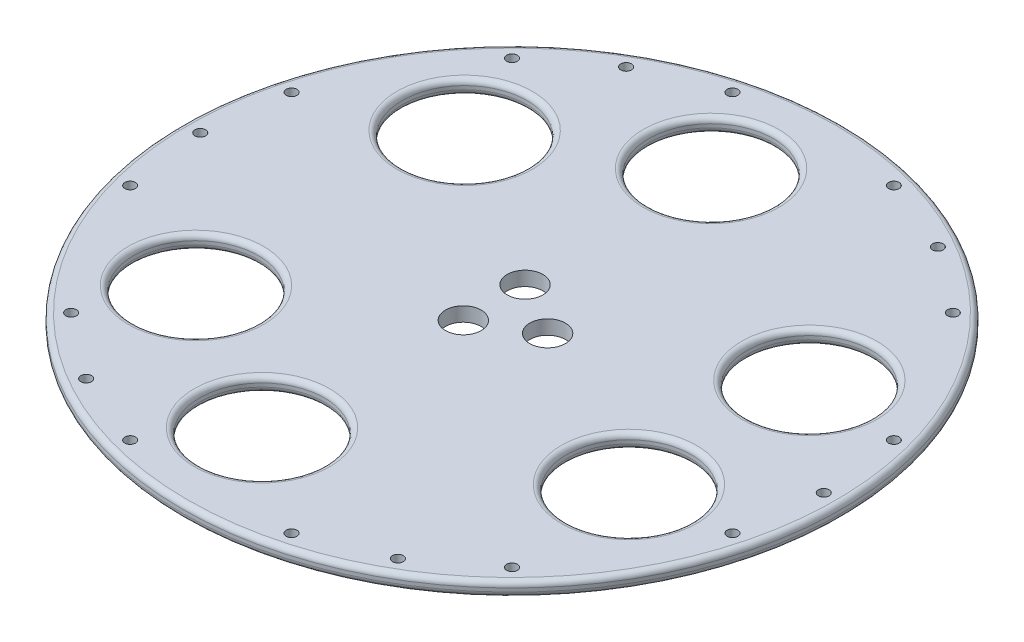
SolidWorks part; units mm, degrees
ref_plane "Front Plane" through (0, 0, 0) normal (0, 0, 1) x (1, 0, 0)
ref_plane "Top Plane" through (0, 0, 0) normal (0, 1, 0) x (1, 0, 0)
ref_plane "Right Plane" through (0, 0, 0) normal (1, 0, 0) x (0, 0, -1)
sketch "Sketch1" plane through (0, 0, 0) normal (0, 1, 0) x (1, 0, 0)
  circle A0 centre (0, 0) radius 92.5
  dimension "D1" = 185
extrude "Boss-Extrude1" add sketch "Sketch1" along normal blind 4
sketch "Sketch2" plane through (0, 4, 0) normal (0, 1, 0) x (1, 0, 0)
  line L0 (0, 0) -> (-51, 0)
  line L1 (0, 0) -> (-43.75, 75.7772)
  line L2 (0, 0) -> (-50.9968, 37.7)
  line L3 (0, 0) -> (-7.1476, 63.02)
  line L4 (0, 0) -> (-7, 0)
  line L5 (0, 0) -> (-5, 8.6603)
  circle A3 centre (-43.75, 75.7772) radius 1.5
  circle A4 centre (-22.6467, 84.5185) radius 1.5
  circle A5 centre (-61.8718, 61.8718) radius 1.5
  circle A6 centre (43.75, 75.7772) radius 1.5
  circle A7 centre (22.6467, 84.5185) radius 1.5
  circle A8 centre (61.8718, 61.8718) radius 1.5
  circle A9 centre (87.5, 0) radius 1.5
  circle A10 centre (84.5185, 22.6467) radius 1.5
  circle A11 centre (84.5185, -22.6467) radius 1.5
  circle A13 centre (-5, 8.6603) radius 5
  circle A14 centre (-50.9968, 37.7) radius 17.5
  circle A15 centre (-7.1476, 63.02) radius 17.5
  circle A16 centre (58.1507, -25.32) radius 17.5
  circle A17 centre (58.1476, 25.3146) radius 17.5
  circle A18 centre (-51.0032, -37.7) radius 17.5
  circle A19 centre (-7.1507, -63.0146) radius 17.5
  circle A23 centre (10, 0) radius 5
  circle A24 centre (-5, -8.6603) radius 5
  circle A25 centre (43.75, -75.7772) radius 1.5
  circle A26 centre (61.8718, -61.8718) radius 1.5
  circle A27 centre (22.6467, -84.5185) radius 1.5
  circle A28 centre (-43.75, -75.7772) radius 1.5
  circle A29 centre (-22.6467, -84.5185) radius 1.5
  circle A30 centre (-61.8718, -61.8718) radius 1.5
  circle A31 centre (-87.5, 0) radius 1.5
  circle A32 centre (-84.5185, -22.6467) radius 1.5
  circle A33 centre (-84.5185, 22.6467) radius 1.5
  point P10 (0, 0)
  point P15 (0, 0)
  point P18 (0, 0)
  point P32 (0, 0)
  point P33 (0, 0)
  point P41 (0, 0)
  point P46 (0, 0)
  point P49 (0, 0)
  point P55 (0, 0)
  dimension "D1" = 35
  dimension "D2" = 35
  dimension "D5" = 2
  dimension "D6" = 2
  dimension "D7" = 3
  dimension "D8" = 6
  dimension "D3" = 60
extrude "Cut-Extrude1" cut sketch "Sketch2" against normal through all
fillet "Fillet1" radius 1.5 14 edges at (58.1476, 4, -7.8146) (58.1476, 0, -7.8146) (-7.1476, 4, -45.52) (-7.1476, 0, -45.52) (-50.9968, 4, -20.2) (-50.9968, 0, -20.2) (-51.0032, 0, 55.2) (-51.0032, 4, 55.2) (-7.1507, 4, 80.5146) (-7.1507, 0, 80.5146) (58.1507, 4, 42.82) (58.1507, 0, 42.82) (0, 4, 92.5) (0, 0, 92.5)
